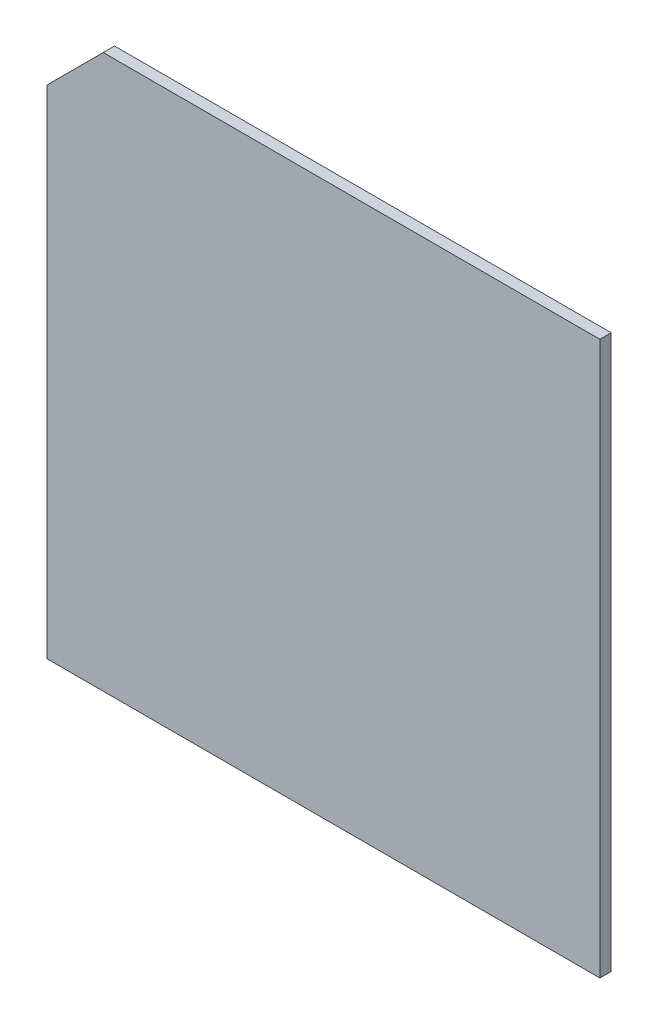
SolidWorks part; units mm, degrees
material "Glass"
ref_plane "Front Plane" through (0, 0, 0) normal (1, 0, 0) x (0, 1, 0)
ref_plane "Top Plane" through (0, 0, 0) normal (0, 0, 1) x (0, 1, 0)
ref_plane "Right Plane" through (0, 0, 0) normal (0, 1, 0) x (-1, 0, 0)
sketch "Sketch1" plane through (0, 0, 0) normal (0, 0, 1) x (0, 1, 0)
  line L0 (44, 49) -> (49, 44)
  line L1 (0, 0) -> (49, 0)
  line L2 (0, 0) -> (0, 49)
  line L3 (0, 49) -> (44, 49)
  line L4 (49, 0) -> (49, 44)
  point P1 (49, 49)
  dimension "D1" = 49
extrude "Boss-Extrude1" add sketch "Sketch1" along normal blind 1
